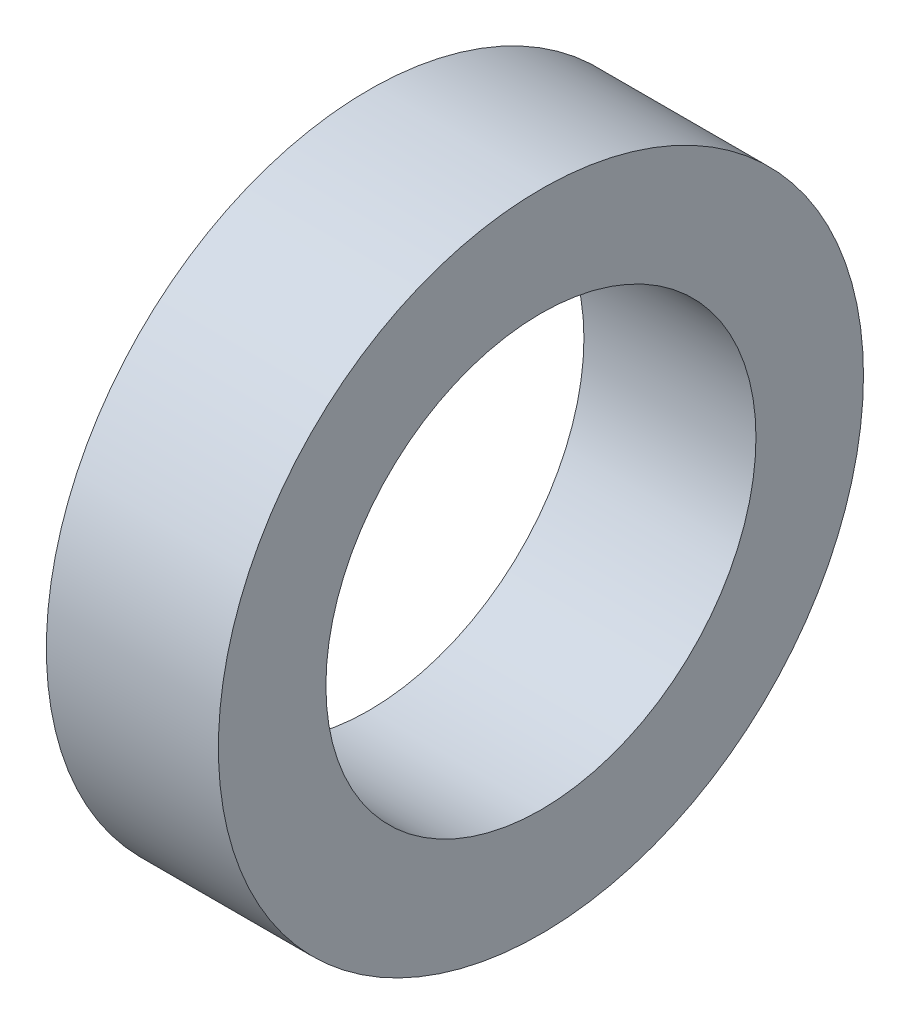
SolidWorks part; units mm, degrees
material "AISI 304"
ref_plane "Front" through (0, 0, 0) normal (0, 0, 1) x (1, 0, 0)
ref_plane "Top" through (0, 0, 0) normal (0, 1, 0) x (1, 0, 0)
ref_plane "Right" through (0, 0, 0) normal (1, 0, 0) x (0, 0, -1)
sketch "Sketch1" plane through (0, 0, 0) normal (1, 0, 0) x (0, 0, -1)
  circle A0 centre (0, 0) radius 7.5
  dimension "D1" = 15
extrude "Boss-Extrude1" add sketch "Sketch1" along normal blind 4
sketch "Sketch2" plane through (4, 0, 0) normal (1, 0, 0) x (0, 0, -1)
  circle A0 centre (0, 0) radius 5
  dimension "D1" = 10
extrude "Cut-Extrude1" cut sketch "Sketch2" against normal through all
